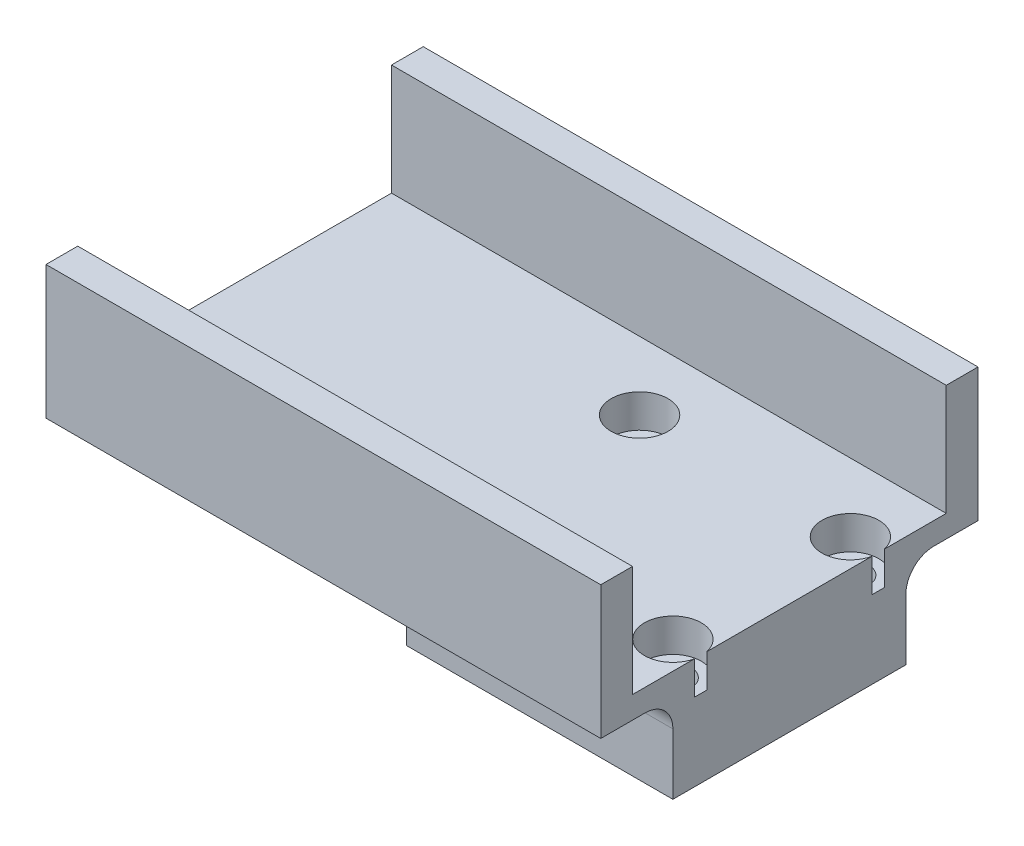
SolidWorks part; units mm, degrees
ref_plane "Front Plane" through (0, 0, 0) normal (0, 0, 1) x (1, 0, 0)
ref_plane "Top Plane" through (0, 0, 0) normal (0, 1, 0) x (1, 0, 0)
ref_plane "Right Plane" through (0, 0, 0) normal (1, 0, 0) x (0, 0, -1)
sketch "Sketch1" plane through (0, 0, 0) normal (0, 1, 0) x (1, 0, 0)
  line L1 (-9.5, 8) -> (9.5, 8) construction
  line L2 (-9.5, 8) -> (-9.5, -8) construction
  line L3 (-9.5, -8) -> (9.5, -8) construction
  line L4 (9.5, 8) -> (9.5, -8) construction
  line L5 (-9.5, 8) -> (9.5, -8) construction
  line L6 (-9.5, -8) -> (9.5, 8) construction
  line L7 (12, 10.5) -> (-12, 10.5)
  line L8 (12, 10.5) -> (12, -10.5)
  line L9 (12, -10.5) -> (-12, -10.5)
  line L10 (-12, 10.5) -> (-12, -10.5)
  line L11 (12, 10.5) -> (-12, -10.5) construction
  line L12 (12, -10.5) -> (-12, 10.5) construction
  circle A0 centre (-9.5, 8) radius 1.625
  circle A1 centre (9.5, 8) radius 1.625
  circle A2 centre (9.5, -8) radius 1.625
  circle A3 centre (-9.5, -8) radius 1.625
  point P0 (0, 0)
  point P10 (0, 0)
  dimension "D3" = 3.25
  dimension "D1" = 24
  dimension "D2" = 21
  dimension "D4" = 19
  dimension "D5" = 16
extrude "Boss-Extrude1" add sketch "Sketch1" along normal blind 8
sketch "Sketch2" plane through (0, 8, 0) normal (0, 1, 0) x (1, 0, 0)
  line L0 (12, -10.5) -> (12, 10.5) construction
  line L1 (12, 17) -> (-38, 17)
  line L2 (12, 17) -> (12, -17)
  line L3 (12, -17) -> (-38, -17)
  line L4 (-38, 17) -> (-38, -17)
  line L5 (12, 17) -> (-38, -17) construction
  line L6 (12, -17) -> (-38, 17) construction
  circle A0 centre (9.5, -8) radius 1.625 construction
  circle A1 centre (-9.5, -8) radius 1.625 construction
  circle A2 centre (9.5, 8) radius 1.625 construction
  circle A3 centre (-9.5, 8) radius 1.625 construction
  circle A4 centre (9.5, -8) radius 1.625
  circle A5 centre (-9.5, -8) radius 1.625
  circle A6 centre (9.5, 8) radius 1.625
  circle A7 centre (-9.5, 8) radius 1.625
  point P0 (-13, 0)
  point P9 (12, 0)
  point P10 (12, 0)
  dimension "D1" = 34
  dimension "D2" = 50
extrude "Boss-Extrude2" add sketch "Sketch2" along normal blind 2
fillet "Fillet2" radius 2.5 3 edges at (0, 8, -10.5) (-12, 8, 0) (0, 8, 10.5)
sketch "Sketch3" plane through (0, 10, 0) normal (0, 1, 0) x (1, 0, 0)
  line L0 (12, -17) -> (12, 17) construction
  line L1 (-38, 17) -> (12, 17)
  line L2 (-38, 17) -> (-38, 14.1384)
  line L3 (-38, 14.1384) -> (12, 14.1384)
  line L4 (12, 17) -> (12, 14.1384)
  line L6 (-38, -17) -> (12, -17)
  line L7 (-38, -17) -> (-38, -14.1384)
  line L8 (-38, -14.1384) -> (12, -14.1384)
  line L9 (12, -17) -> (12, -14.1384)
  dimension "D1" = 2.8616
extrude "Boss-Extrude3" add sketch "Sketch3" along normal blind 10
sketch "Sketch4" plane through (0, 10, 0) normal (0, 1, 0) x (1, 0, 0)
  circle A0 centre (-9.5, 8) radius 2.5625
  circle A1 centre (9.5, 8) radius 2.5625
  circle A2 centre (9.5, -8) radius 2.5625
  circle A3 centre (-9.5, -8) radius 2.5625
  dimension "D1" = 5.125
extrude "Cut-Extrude3" cut sketch "Sketch4" against normal blind 3
